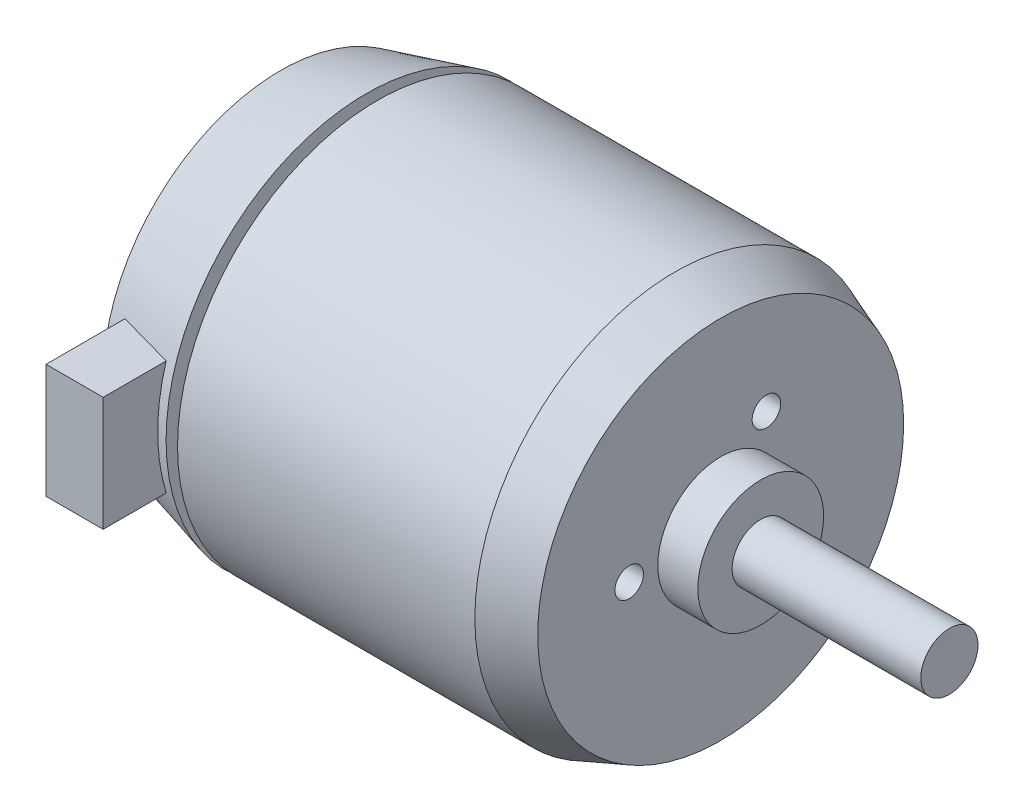
SolidWorks part; units mm, degrees
material "Material"
ref_plane "Front Plane" through (0, 0, 0) normal (0, 0, 1) x (1, 0, 0)
ref_plane "Top Plane" through (0, 0, 0) normal (0, 1, 0) x (1, 0, 0)
ref_plane "Right Plane" through (0, 0, 0) normal (1, 0, 0) x (0, 0, -1)
sketch "Sketch1" plane through (0, 0, 0) normal (0, 0, 1) x (1, 0, 0)
  line L0 (0, 15.5) -> (0, 0)
  line L1 (0, 0) -> (38.5, 0)
  line L2 (38.5, 0) -> (38.5, 17.5)
  line L3 (38.5, 17.5) -> (8.5, 17.5)
  line L4 (8.5, 17.5) -> (8.5, 12.5)
  line L5 (8.5, 12.5) -> (7.5, 12.5)
  line L6 (7.5, 12.5) -> (7.5, 17.5)
  line L7 (7.5, 17.5) -> (0, 15.5)
  line L8 (0, 0) -> (38.5, 0) construction
revolve "Revolve1" add sketch "Sketch1" angle 360 about L8
ref_plane "Plane1" through (0, 0, 22) normal (0, 0, 1) x (1, 0, 0)
sketch "Sketch2" plane through (0, 0, 22) normal (0, 0, 1) x (1, 0, 0)
  line L0 (6.5, -5) -> (6.5, 5)
  line L1 (6.5, 5) -> (1.5, 5)
  line L2 (1.5, 5) -> (1.5, -5)
  line L3 (1.5, -5) -> (6.5, -5)
extrude "Boss-Extrude1" add sketch "Sketch2" against normal up to next
sketch "Sketch3" plane through (0, 0, 0) normal (-1, 0, 0) x (0, 0, 1)
  circle A0 centre (0, 0) radius 4
extrude "Boss-Extrude2" add sketch "Sketch3" along normal blind 1
sketch "Sketch4" plane through (38.5, 0, 0) normal (1, 0, 0) x (0, 0, -1)
  circle A0 centre (0, 0) radius 5.5
extrude "Boss-Extrude3" add sketch "Sketch4" along normal blind 3.5
sketch "Sketch5" plane through (42, 0, 0) normal (1, 0, 0) x (0, 0, -1)
  circle A0 centre (0, 0) radius 2.5
extrude "Boss-Extrude4" add sketch "Sketch5" along normal blind 16.5
hole_wizard "Ø2.5 (2.5) Diameter Hole1" positions "Sketch7" profile "Sketch6" hole size "Ø2.5" standard "ANSI Metric"
sketch "Sketch7" plane through (38.5, 0, 0) normal (1, 0, 0) x (0, 0, -1)
  point P0 (4, -6.9282)
  point P1 (4, 6.9282)
  point P2 (-8, 0)
sketch "Sketch6" plane through (38.5, -6.9282, -4) normal (0, 1, 0) x (0, 0, -1)
  line L0 (0, 0) -> (0, 28.7511)
  line L1 (0, 28.7511) -> (1.25, 28)
  line L2 (1.25, 28) -> (1.25, 0)
  line L5 (1.25, 0) -> (0, 0)
  line L10 (0, 28.7511) -> (-1.25, 28) construction
  line L11 (0, -6.35) -> (0, 107.95) construction
  dimension "Hole Dia." = 2.5
  dimension "Hole Depth" = 28
  dimension "Drill Angle" = 118
hole_wizard "Ø3.0 (3) Diameter Hole1" positions "Sketch9" profile "Sketch8" hole size "Ø3.0" standard "ANSI Metric"
sketch "Sketch9" plane through (0, 0, 0) normal (-1, 0, 0) x (0, 0, 1)
  point P0 (-6.7175, -6.7175)
  point P1 (8.8388, -8.8388)
  point P2 (6.7175, 6.7175)
  point P3 (-8.8388, 8.8388)
sketch "Sketch8" plane through (0, -6.7175, -6.7175) normal (0, 1, 0) x (0, 0, 1)
  line L0 (0, 0) -> (0, 28.9013)
  line L1 (0, 28.9013) -> (1.5, 28)
  line L2 (1.5, 28) -> (1.5, 0)
  line L5 (1.5, 0) -> (0, 0)
  line L10 (0, 28.9013) -> (-1.5, 28) construction
  line L11 (0, -6.35) -> (0, 107.95) construction
  dimension "Hole Dia." = 3
  dimension "Hole Depth" = 28
  dimension "Drill Angle" = 118
chamfer "Chamfer1" distance 1.5 angle 69.444 1 edges at (38.5, 0, -17.5)
